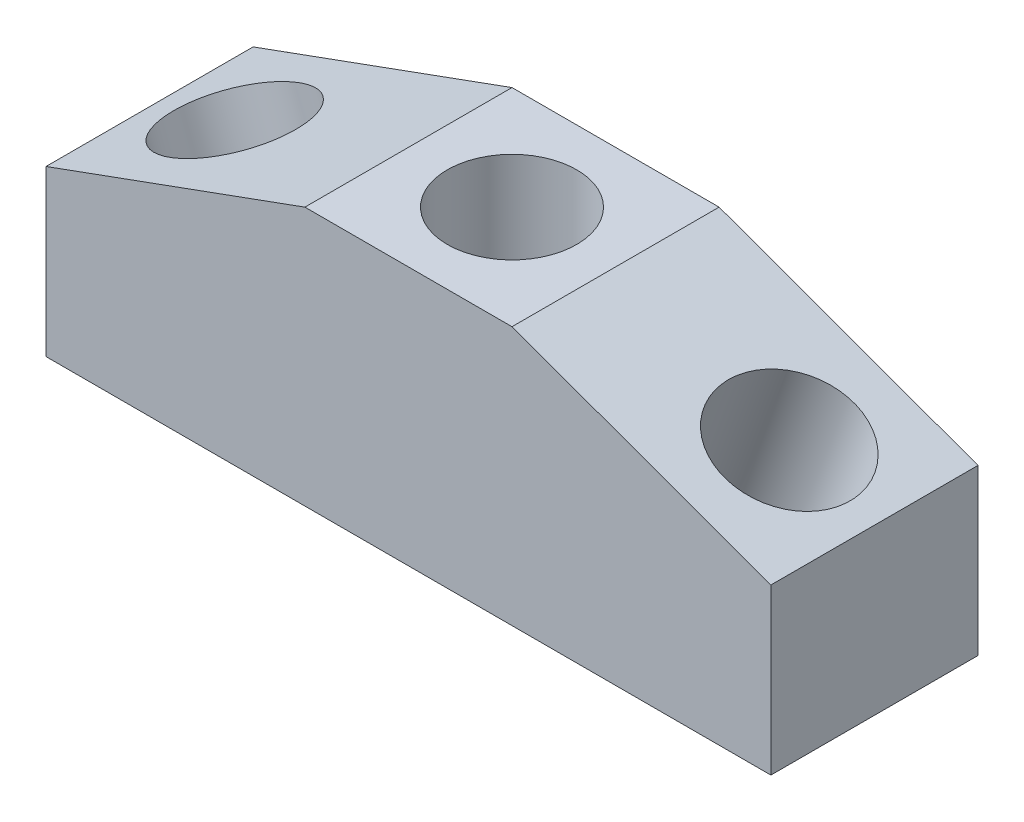
SolidWorks part; units mm, degrees
ref_plane "前视基准面" through (0, 0, 0) normal (0, 0, 1) x (1, 0, 0)
ref_plane "上视基准面" through (0, 0, 0) normal (0, 1, 0) x (1, 0, 0)
ref_plane "右视基准面" through (0, 0, 0) normal (1, 0, 0) x (0, 0, -1)
sketch "草图1" plane through (0, 0, 0) normal (0, 0, 1) x (1, 0, 0)
  line L0 (0, 0) -> (28, 0)
  line L1 (10, 10) -> (18, 10)
  line L2 (18, 10) -> (28, 6.3603)
  line L3 (28, 6.3603) -> (28, 0)
  line L4 (10, 10) -> (0, 6.3603)
  line L5 (0, 6.3603) -> (0, 0)
  dimension "D1" = 28
  dimension "D2" = 8
  dimension "D3" = 10
  dimension "D4" = 140
extrude "凸台-拉伸1" add sketch "草图1" against normal blind 8
hole_wizard "M6 螺纹孔1" positions "草图4" profile "草图6" tap size "M6" standard "GB" end condition through all
sketch "草图4" plane through (0, 10, 0) normal (0, 1, 0) x (1, 0, 0)
  point P0 (14, 4)
sketch "草图6" plane through (14, 10, -4) normal (1, 0, 0) x (0, 0, 1)
  line L0 (0, 0) -> (0, 10)
  line L1 (0, 10) -> (2.5, 10)
  line L2 (2.5, 10) -> (2.5, 0)
  line L5 (2.5, 0) -> (0, 0)
  line L11 (0, -6.35) -> (0, 107.95) construction
  dimension "通孔螺纹孔钻头直径" = 5
  dimension "通孔螺纹孔钻头深度" = 10
cosmetic thread "孔螺蚊线1" parameters "D2"=6
hole_wizard "M6 螺纹孔2" positions "草图7" profile "草图8" tap size "M6" standard "GB" end condition through all
sketch "草图7" plane through (5.3195, 14.6153, 0) normal (0.342, 0.9397, 0) x (0.9397, -0.342, 0)
  line L0 (24.136, 8) -> (24.136, 0) construction
  point P0 (20.636, 4)
  dimension "D1" = 3.5
sketch "草图8" plane through (24.7111, 7.5574, -4) normal (0, 0, 1) x (-0.9397, 0.342, 0)
  line L0 (0, 0) -> (0, 15.5533)
  line L1 (0, 15.5533) -> (2.5, 15.5533)
  line L2 (2.5, 15.5533) -> (2.5, 0)
  line L5 (2.5, 0) -> (0, 0)
  line L11 (0, -6.35) -> (0, 107.95) construction
  dimension "通孔螺纹孔钻头直径" = 5
  dimension "通孔螺纹孔钻头深度" = 15.5533
cosmetic thread "孔螺蚊线2"
hole_wizard "M6 螺纹孔3" positions "草图9" profile "草图10" tap size "M6" standard "GB" end condition through all
sketch "草图9" plane through (-2.0442, 5.6163, 0) normal (-0.342, 0.9397, 0) x (0.9397, 0.342, 0)
  line L0 (2.1753, 8) -> (2.1753, 0) construction
  point P0 (5.6753, 4)
  dimension "D1" = 3.5
sketch "草图10" plane through (3.2889, 7.5574, -4) normal (0, 0, 1) x (-0.9397, -0.342, 0)
  line L0 (0, 0) -> (0, 15.5533)
  line L1 (0, 15.5533) -> (2.5, 15.5533)
  line L2 (2.5, 15.5533) -> (2.5, 0)
  line L5 (2.5, 0) -> (0, 0)
  line L11 (0, -6.35) -> (0, 107.95) construction
  dimension "通孔螺纹孔钻头直径" = 5
  dimension "通孔螺纹孔钻头深度" = 15.5533
cosmetic thread "孔螺蚊线3" parameters "D2"=6
